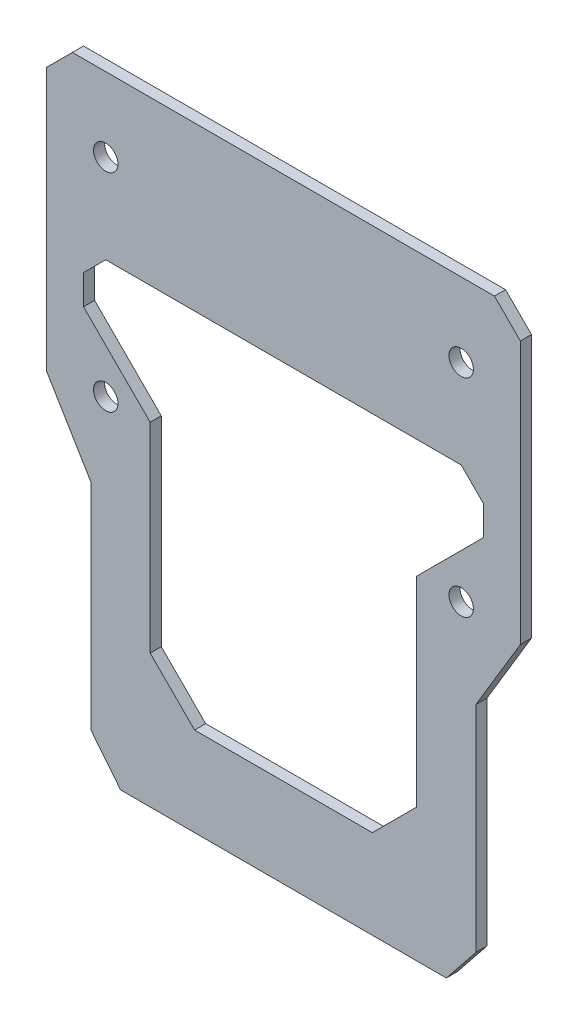
SolidWorks part; units mm, degrees
material "碳纤维板_1600kg_m3"
ref_plane "前视基准面" through (0, 0, 0) normal (0, 0, 1) x (1, 0, 0)
ref_plane "上视基准面" through (0, 0, 0) normal (0, 1, 0) x (1, 0, 0)
ref_plane "右视基准面" through (0, 0, 0) normal (1, 0, 0) x (0, 0, -1)
other "Configuration Table"
sketch "草图1" plane through (0, 0, 0) normal (0, 0, 1) x (1, 0, 0)
  line L92 (-22, 0) -> (22, 0)
  line L93 (22, 0) -> (26, 5)
  line L94 (26, 5) -> (26, 34)
  line L95 (26, 34) -> (32, 44)
  line L96 (32, 44) -> (32, 79.5)
  line L97 (32, 79.5) -> (28, 83.5)
  line L98 (28, 83.5) -> (-28, 83.5)
  line L99 (-28, 83.5) -> (-32, 79.5)
  line L100 (-32, 79.5) -> (-32, 44)
  line L101 (-32, 44) -> (-26, 34)
  line L102 (-26, 34) -> (-26, 5)
  line L103 (-26, 5) -> (-22, 0)
  line L104 (-24, 61) -> (24, 61)
  line L105 (24, 61) -> (27, 58)
  line L106 (27, 58) -> (27, 54)
  line L107 (27, 54) -> (18, 45)
  line L108 (18, 45) -> (18, 18)
  line L109 (18, 18) -> (12, 12)
  line L110 (12, 12) -> (-12, 12)
  line L111 (-12, 12) -> (-18, 18)
  line L112 (-18, 18) -> (-18, 45)
  line L113 (-18, 45) -> (-27, 54)
  line L114 (-27, 54) -> (-27, 58)
  line L115 (-27, 58) -> (-24, 61)
  circle A20 centre (-24, 45) radius 1.65
  circle A22 centre (24, 45) radius 1.65
  circle A24 centre (-24, 73) radius 1.65
  circle A25 centre (24, 73) radius 1.65
extrude "两段开窗短吊舱侧板" add sketch "草图1" along normal blind 1.5
sketch "草图3" plane through (0, 0, 0) normal (0, 0, 1) x (1, 0, 0)
  line L0 (-100, 83) -> (100, 83)
  line L1 (100, 83) -> (100, 85)
  line L2 (100, 85) -> (-100, 85)
  line L3 (-100, 85) -> (-100, 83)
extrude "底板加厚上沿退让0p5" cut sketch "草图3" along normal blind 1.5
